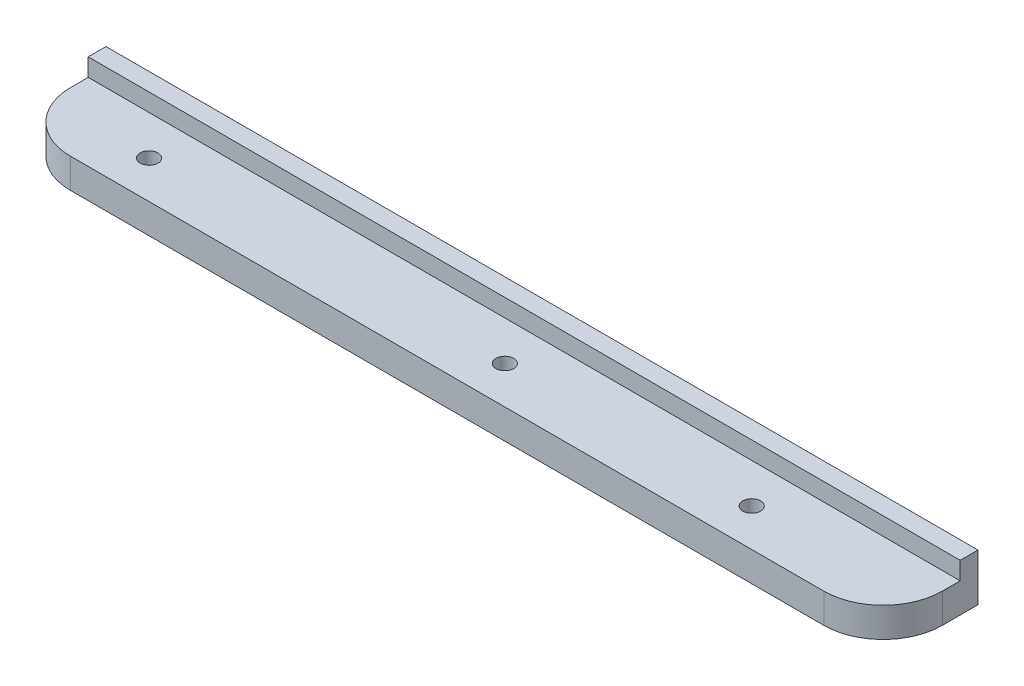
SolidWorks part; units mm, degrees
ref_plane "Front Plane" through (0, 0, 0) normal (0, 0, 1) x (1, 0, 0)
ref_plane "Top Plane" through (0, 0, 0) normal (0, 1, 0) x (1, 0, 0)
ref_plane "Right Plane" through (0, 0, 0) normal (1, 0, 0) x (0, 0, -1)
sketch "Sketch2" plane through (0, 0, 0) normal (0, 1, 0) x (1, 0, 0)
  line L0 (79.8329, 11.2298) -> (51.3329, 11.2298)
  line L1 (-67.1671, 37.2298) -> (79.8329, 37.2298)
  line L2 (-67.1671, 37.2298) -> (-67.1671, 11.2298)
  line L3 (51.3329, 11.2298) -> (9.7229, 11.2298)
  line L4 (79.8329, 37.2298) -> (79.8329, 11.2298)
  line L5 (9.7229, 11.2298) -> (-67.1671, 11.2298)
  line L6 (51.3329, 11.2298) -> (-50.2671, 11.2298)
  line L7 (-50.2671, 11.2298) -> (-50.2671, 17.5798)
  line L8 (-50.2671, 17.5798) -> (9.7229, 17.5798)
  line L9 (9.7229, 17.5798) -> (51.3329, 17.5798)
  circle A0 centre (9.7229, 17.5798) radius 1.5
  circle A1 centre (51.3329, 17.5798) radius 1.5
  circle A2 centre (-50.2671, 17.5798) radius 1.5
  dimension "D6" = 3
  dimension "D7" = 3
  dimension "D8" = 3
  dimension "D1" = 147
  dimension "D2" = 26
  dimension "D3" = 28.5
  dimension "D4" = 101.6
  dimension "D5" = 41.61
extrude "Boss-Extrude1" add sketch "Sketch2" along normal blind 5
sketch "Sketch3" plane through (0, 5, 0) normal (0, 1, 0) x (1, 0, 0)
  line L0 (-67.1671, 37.2298) -> (-67.1671, 11.2298) construction
  line L1 (-67.1671, 24.2298) -> (79.8329, 24.2298)
  line L2 (-67.1671, 24.2298) -> (-67.1671, 27.2298)
  line L3 (-67.1671, 27.2298) -> (79.8329, 27.2298)
  line L4 (79.8329, 24.2298) -> (79.8329, 27.2298)
  line L5 (79.8329, 37.2298) -> (79.8329, 11.2298) construction
  dimension "D1" = 3
extrude "Boss-Extrude2" add sketch "Sketch3" along normal blind 3
fillet "Fillet1" radius 10 2 edges at (-67.1671, 2.5, -11.2298) (-67.1671, 2.5, -37.2298)
fillet "Fillet2" radius 10 2 edges at (79.8329, 2.5, -11.2298) (79.8329, 2.5, -37.2298)
sketch "Sketch4" plane through (0, 0, -37.2298) normal (0, 0, -1) x (-1, 0, 0)
  line L1 (111.4458, -45.7652) -> (98.7713, -45.7652)
  line L2 (111.4458, -45.7652) -> (111.4458, -41.9561)
  line L3 (111.4458, -41.9561) -> (98.7713, -41.9561)
  line L4 (98.7713, -45.7652) -> (98.7713, -41.9561)
  line L5 (98.7713, -41.9561) -> (-95.4975, -41.9561)
  line L6 (98.7713, -41.9561) -> (98.7713, 30.7698)
  line L7 (98.7713, 30.7698) -> (-95.4975, 30.7698)
  line L8 (-95.4975, -41.9561) -> (-95.4975, 30.7698)
  line M1 (57.1671, 5) -> (-69.8329, 5)
  line M2 (-69.8329, 5) -> (-69.8329, 0)
  line M3 (-69.8329, 0) -> (57.1671, 0)
  line M4 (57.1671, 0) -> (57.1671, 5)
extrude "Cut-Extrude1" cut sketch "Sketch4" against normal blind 10 contours M4 M1 M2 M3 | L8 L5 L6 L7 M1 M4 M3 M2
